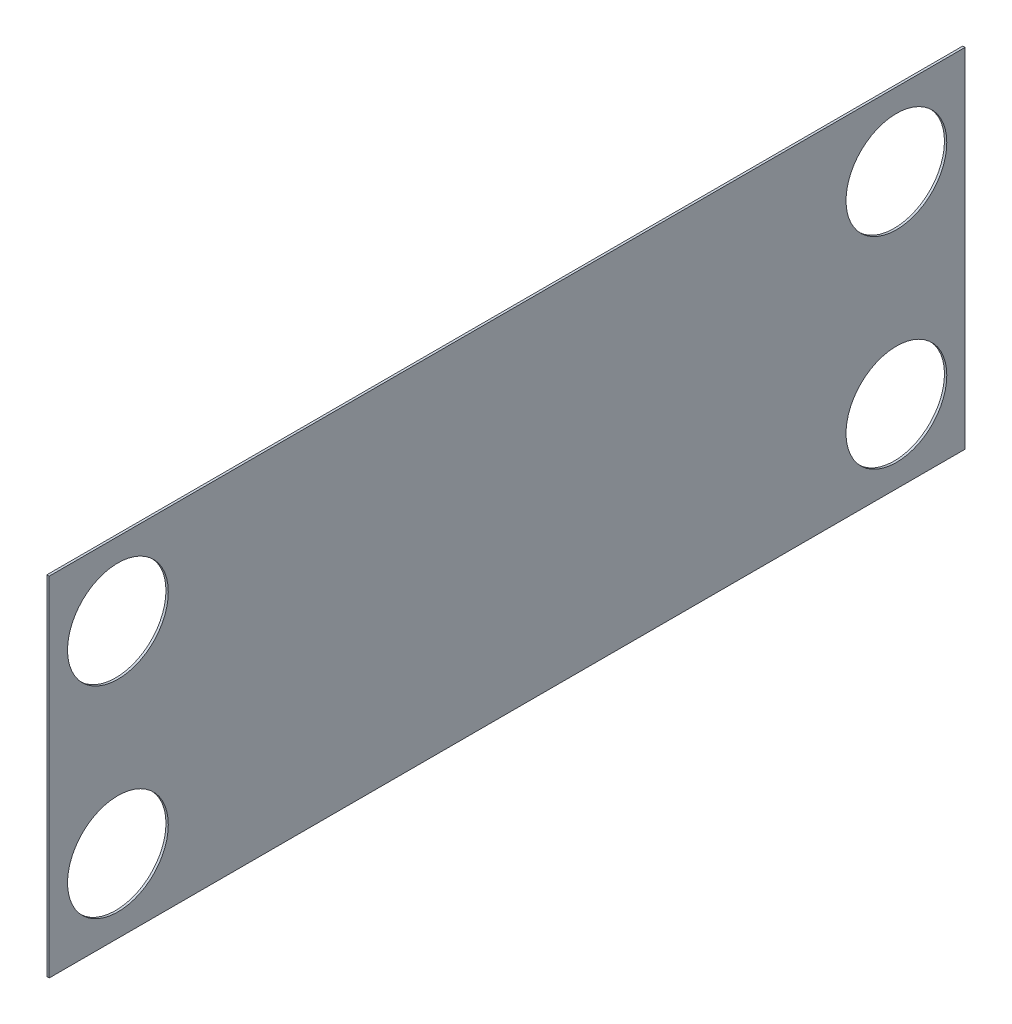
SolidWorks part; units mm, degrees
material "Low Carbon Steel"
ref_plane "Front Plane" through (0, 0, 0) normal (0, 0, 1) x (1, 0, 0)
ref_plane "Top Plane" through (0, 0, 0) normal (0, 1, 0) x (1, 0, 0)
ref_plane "Right Plane" through (0, 0, 0) normal (1, 0, 0) x (0, 0, -1)
sketch "Sketch1" plane through (0, 0, 0) normal (1, 0, 0) x (0, 0, -1)
  line L0 (50, 19) -> (-50, -19) construction
  line L1 (-50, 19) -> (50, 19)
  line L2 (-50, 19) -> (-50, -19)
  line L3 (-50, -19) -> (50, -19)
  line L4 (50, 19) -> (50, -19)
  dimension "D1" = 100
  dimension "D2" = 38
extrude "Boss-Extrude1" add sketch "Sketch1" along normal blind 0.254
hole_wizard "M10 Clearance Hole1" positions "Sketch2" profile "Sketch3" hole size "M10" standard "Peddi DIN" end condition through all
sketch "Sketch2" plane through (0.254, 0, 0) normal (1, 0, 0) x (0, 0, -1)
  line L0 (42.5, 11) -> (42.5, -11) construction
  line L1 (42.5, -11) -> (-42.5, 11) construction
  line L2 (-42.5, 11) -> (-42.5, -11) construction
  line L3 (-42.5, -11) -> (42.5, -11) construction
  point P0 (-42.5, 11)
  point P2 (-42.5, -11)
  point P4 (42.5, 11)
  point P6 (42.5, -11)
  dimension "D1" = 22
  dimension "D2" = 85
sketch "Sketch3" plane through (0.254, 11, 42.5) normal (0, 1, 0) x (0, 0, -1)
  line L0 (0, 0) -> (0, 0.254)
  line L1 (0, 0.254) -> (5.5, 0.254)
  line L2 (5.5, 0.254) -> (5.5, 0)
  line L5 (5.5, 0) -> (0, 0)
  line L11 (0, -6.35) -> (0, 107.95) construction
  dimension "Thru Hole Dia." = 11
  dimension "Thru Hole Depth" = 0.254
other "Freeze***"
